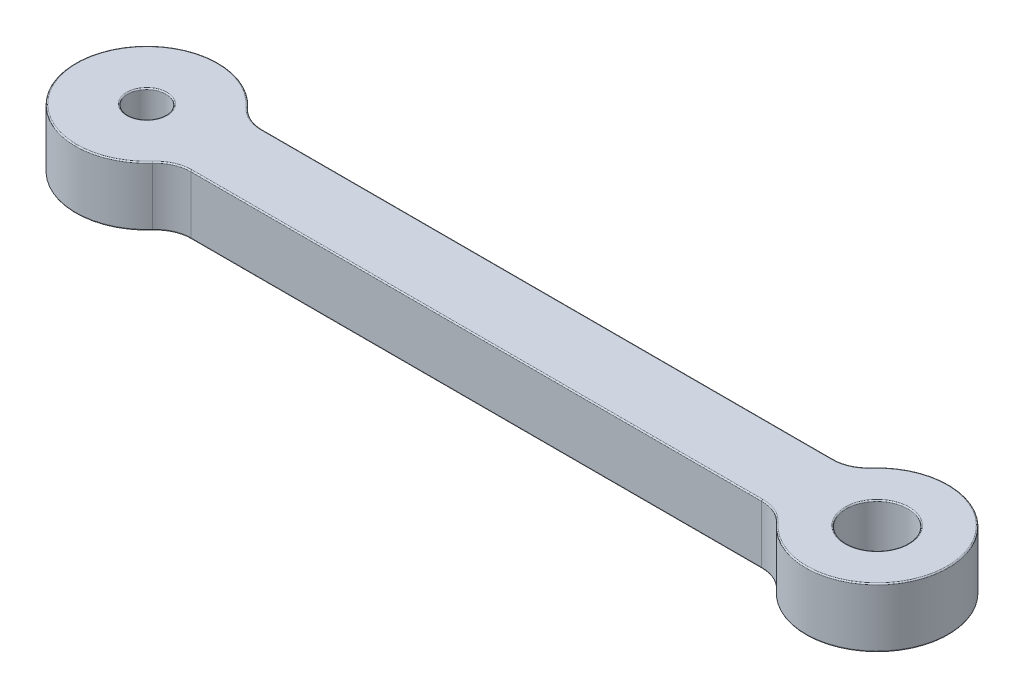
SolidWorks part; units mm, degrees
ref_plane "Front Plane" through (0, 0, 0) normal (0, 0, 1) x (1, 0, 0)
ref_plane "Top Plane" through (0, 0, 0) normal (0, 1, 0) x (1, 0, 0)
ref_plane "Right Plane" through (0, 0, 0) normal (1, 0, 0) x (0, 0, -1)
sketch "Sketch1" plane through (0, 0, 0) normal (0, 1, 0) x (1, 0, 0)
  line L0 (0, 0) -> (1.6, 0)
  line L1 (6.7082, 3) -> (54.7082, 3)
  line L2 (6.7082, -3) -> (54.7082, -3)
  line L3 (0, 3) -> (61.4164, 3) construction
  line L4 (54.7082, 6) -> (54.7082, -6) construction
  line L5 (0, 0) -> (61.4164, 0) construction
  line L6 (0, -3) -> (61.4164, -3) construction
  arc A0 (4.4721, 4) -> (4.4721, -4) centre (0, 0) ccw
  circle A1 centre (0, 0) radius 1.6
  circle A2 centre (61.4164, 0) radius 2.6
  arc A3 (56.9443, -4) -> (56.9443, 4) centre (61.4164, 0) ccw
  arc A4 (56.9443, -4) -> (54.7082, -3) centre (54.7082, -6) ccw
  arc A5 (54.7082, 3) -> (56.9443, 4) centre (54.7082, 6) ccw
  arc A6 (6.7082, -3) -> (4.4721, -4) centre (6.7082, -6) ccw
  arc A7 (6.7082, 3) -> (4.4721, 4) centre (6.7082, 6) cw
  dimension "D1" = 12
  dimension "D2" = 3.2
  dimension "D4" = 12
  dimension "D5" = 5.2
  dimension "D8" = 3
  dimension "D3" = 48
  dimension "D6" = 3
  dimension "D7" = 3
extrude "Boss-Extrude1" add sketch "Sketch1" along normal blind 5 contours L1 A7 A0 A6 L2 A4 A3 A5 A1 A2
fillet "Fillet1" radius 0.1 20 edges at (5.4835, 0, -3.2614) (-6, 0, 0) (5.4835, 0, 3.2614) (30.7082, 0, 3) (55.9329, 0, 3.2614) (67.4164, 0, 0) (55.9329, 0, -3.2614) (30.7082, 0, -3) (61.4164, 0, 2.6) (0, 0, 1.6) (55.9329, 5, -3.2614) (67.4164, 5, 0) (55.9329, 5, 3.2614) (30.7082, 5, 3) (5.4835, 5, 3.2614) (-6, 5, 0) (5.4835, 5, -3.2614) (30.7082, 5, -3) (61.4164, 5, 2.6) (0, 5, 1.6)
